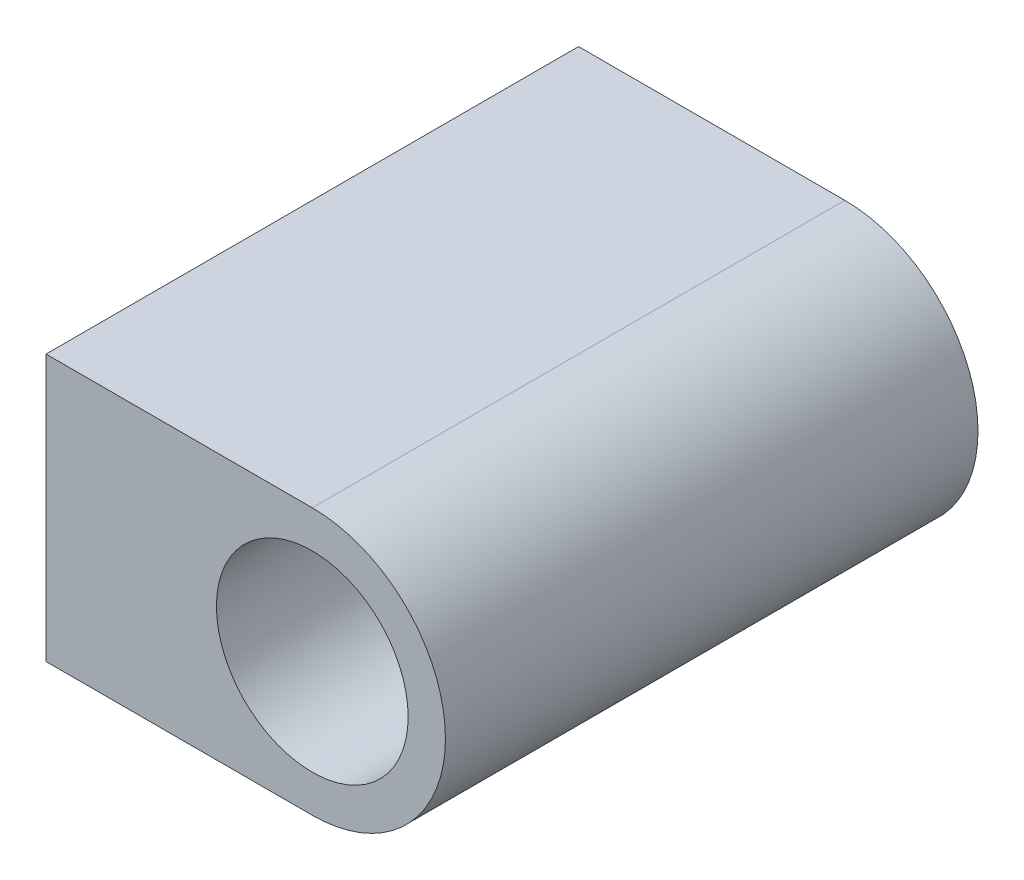
SolidWorks part; units mm, degrees
ref_plane "前视基准面" through (0, 0, 0) normal (0, 0, 1) x (1, 0, 0)
ref_plane "上视基准面" through (0, 0, 0) normal (0, 1, 0) x (1, 0, 0)
ref_plane "右视基准面" through (0, 0, 0) normal (1, 0, 0) x (0, 0, -1)
other "Configuration Table"
sketch "草图2" plane through (0, 0, 0) normal (0, 0, 1) x (1, 0, 0)
  line L0 (0, 0) -> (-5, 0)
  line L1 (-5, 0) -> (-5, -5)
  line L2 (-5, -5) -> (0, -5)
  arc A0 (0, 0) -> (0, -5) centre (0, -2.5) cw
  circle A1 centre (0, -2.5) radius 1.8
extrude "凸台-拉伸1" add sketch "草图2" along normal blind 10
